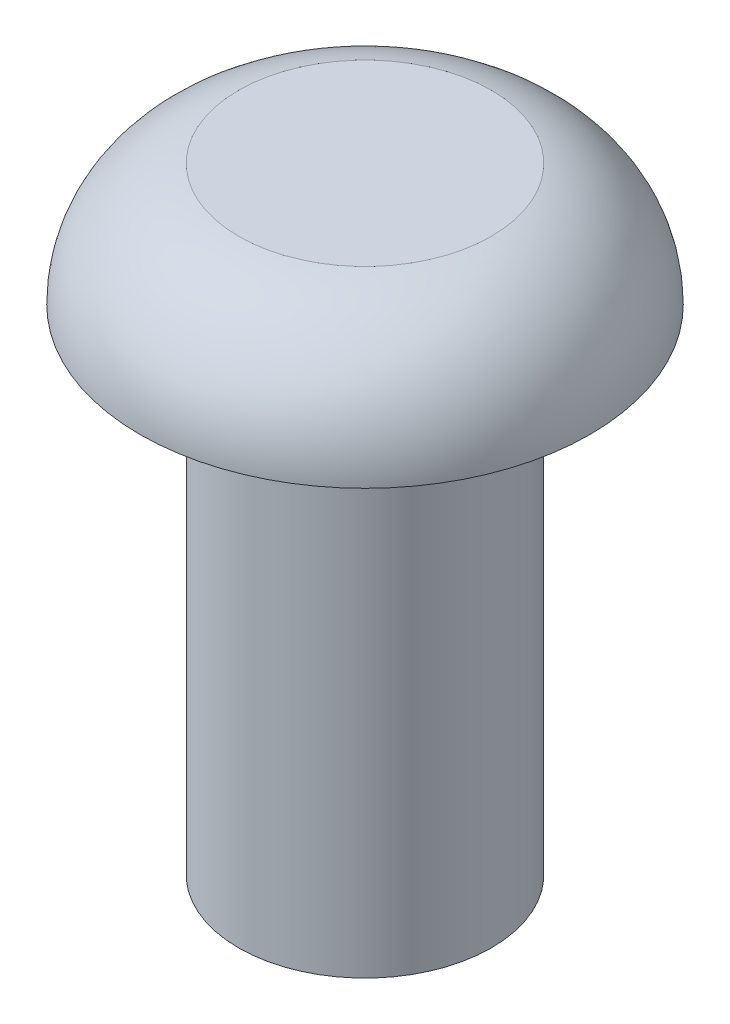
SolidWorks part; units mm, degrees
ref_plane "Front Plane" through (0, 0, 0) normal (0, 0, 1) x (1, 0, 0)
ref_plane "Top Plane" through (0, 0, 0) normal (0, 1, 0) x (1, 0, 0)
ref_plane "Right Plane" through (0, 0, 0) normal (1, 0, 0) x (0, 0, -1)
sketch "Sketch1" plane through (0, 0, 0) normal (0, 0, 1) x (1, 0, 0)
  line L0 (0, 0) -> (1.6, 0) construction
  line L1 (1.6, 0) -> (1.6, 6.25) construction
  line L2 (0, 0) -> (1.6, 0)
  line L3 (1.6, 0) -> (1.6, 6.25)
  line L4 (1.6, 6.25) -> (2.8479, 6.25)
  line L5 (1.6, 7.7984) -> (0, 7.7984)
  line L6 (0, 7.7984) -> (0, 0)
  arc A0 (2.8479, 6.25) -> (1.6, 7.7984) centre (1.2634, 6.25) ccw
  dimension "D1" = 1.6
  dimension "D2" = 6.25
revolve "Revolve1" add sketch "Sketch1" angle 360 about L6
